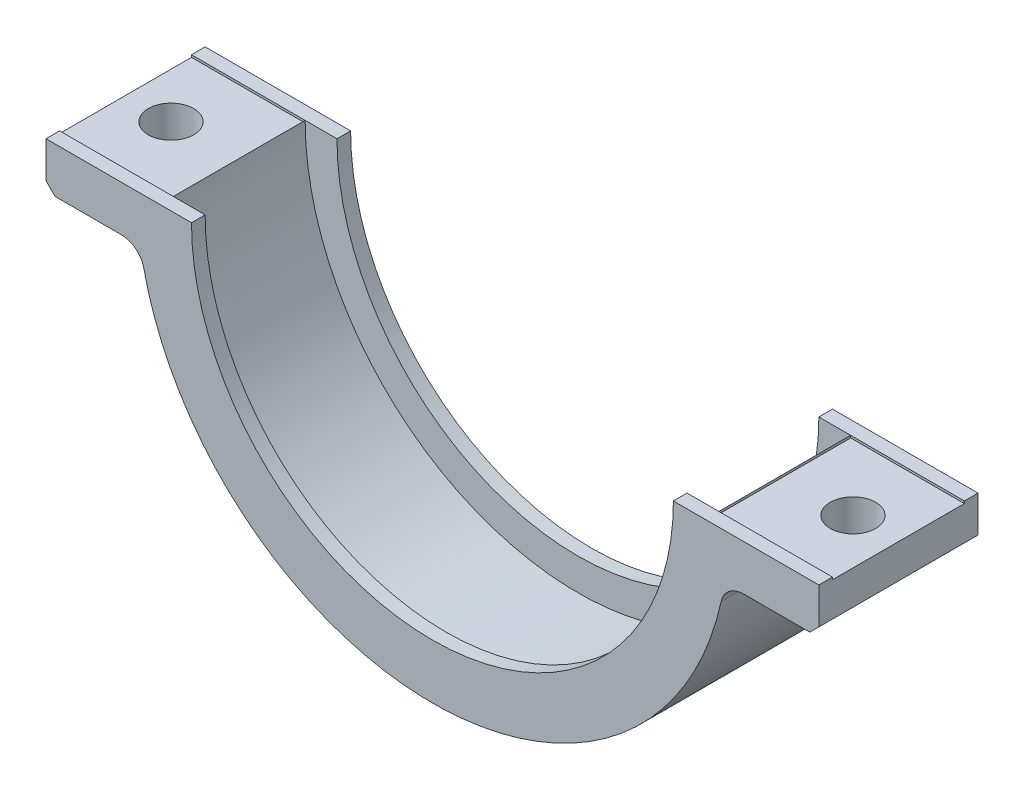
SolidWorks part; units mm, degrees
ref_plane "Płaszczyzna przednia" through (0, 0, 0) normal (0, 0, 1) x (1, 0, 0)
ref_plane "Płaszczyzna górna" through (0, 0, 0) normal (0, 1, 0) x (1, 0, 0)
ref_plane "Płaszczyzna prawa" through (0, 0, 0) normal (1, 0, 0) x (0, 0, -1)
sketch "Szkic1" plane through (0, 0, 0) normal (0, 0, 1) x (1, 0, 0)
  line L0 (-65, 0) -> (-60, 0)
  line L1 (60, 0) -> (65, 0)
  line L2 (-65, 0) -> (-85, 0)
  line L3 (-85, 0) -> (-85, -8)
  line L4 (-83, -10) -> (-68.374, -10)
  line L5 (0, 0) -> (0, -5.7324)
  line L6 (83, -10) -> (68.374, -10)
  line L7 (85, 0) -> (85, -8)
  line L8 (65, 0) -> (85, 0)
  line L9 (-85, -8) -> (-83, -10)
  line L10 (85, -8) -> (83, -10)
  arc A0 (-60, 0) -> (60, 0) centre (0, 0) ccw
  arc A1 (-63.4901, -13.9286) -> (63.4901, -13.9286) centre (0, 0) ccw
  circle A2 centre (0, 0) radius 65 construction
  circle A3 centre (0, 0) radius 60 construction
  arc A4 (68.374, -10) -> (63.4901, -13.9286) centre (68.374, -15) ccw
  arc A5 (-68.374, -10) -> (-63.4901, -13.9286) centre (-68.374, -15) cw
  point P2 (85, -10)
  point P11 (-85, -10)
  point P18 (64.2262, -10)
  point P21 (-64.2262, -10)
  dimension "D1" = 120
  dimension "D5" = 5
  dimension "D3" = 20
  dimension "D4" = 10
  dimension "D2" = 5
extrude "Dodanie-wyciągnięcie1" add sketch "Szkic1" along normal mid plane 29 contours L4 A5 A1 A4 L6 L10 L7 L8 L1 A0 L0 L2 L3 L9
sketch "Szkic2" plane through (0, 0, 14.5) normal (0, 0, 1) x (1, 0, 0)
  line L0 (-65, 0) -> (-60, 0)
  line L1 (60, 0) -> (65, 0)
  line L2 (-65, 0) -> (-85, 0)
  line L3 (-85, 0) -> (-85, -8)
  line L4 (-83, -10) -> (-68.374, -10)
  line L6 (83, -10) -> (68.374, -10)
  line L7 (85, 0) -> (85, -8)
  line L8 (65, 0) -> (85, 0)
  line L9 (-85, -8) -> (-83, -10)
  line L10 (85, -8) -> (83, -10)
  line L11 (-60, 0) -> (-53, 0)
  line L12 (53, 0) -> (60, 0)
  arc A1 (-63.4901, -13.9286) -> (63.4901, -13.9286) centre (0, 0) ccw
  arc A2 (68.374, -10) -> (63.4901, -13.9286) centre (68.374, -15) ccw
  arc A3 (-68.374, -10) -> (-63.4901, -13.9286) centre (-68.374, -15) cw
  arc A4 (-53, 0) -> (53, 0) centre (0, 0) ccw
  point P1 (85, -10)
  point P8 (-85, -10)
  dimension "D4" = 5
  dimension "D9" = 106
  dimension "D2" = 20
  dimension "D3" = 10
  dimension "D5" = 2
  dimension "D6" = 2
  dimension "D7" = 2
  dimension "D8" = 2
extrude "Dodanie-wyciągnięcie2" add sketch "Szkic2" along normal blind 3
sketch "Szkic3" plane through (0, 0, -14.5) normal (0, 0, -1) x (-1, 0, 0)
  line L0 (-65, 0) -> (-60, 0)
  line L1 (60, 0) -> (65, 0)
  line L2 (-65, 0) -> (-85, 0)
  line L3 (-85, 0) -> (-85, -8)
  line L4 (-83, -10) -> (-68.374, -10)
  line L5 (83, -10) -> (68.374, -10)
  line L6 (85, 0) -> (85, -8)
  line L7 (65, 0) -> (85, 0)
  line L8 (-85, -8) -> (-83, -10)
  line L9 (85, -8) -> (83, -10)
  line L10 (-60, 0) -> (-53, 0)
  line L11 (53, 0) -> (60, 0)
  arc A0 (-63.4901, -13.9286) -> (63.4901, -13.9286) centre (0, 0) ccw
  arc A1 (68.374, -10) -> (63.4901, -13.9286) centre (68.374, -15) ccw
  arc A2 (-68.374, -10) -> (-63.4901, -13.9286) centre (-68.374, -15) cw
  arc A3 (-53, 0) -> (53, 0) centre (0, 0) ccw
  point P1 (85, -10)
  point P8 (-85, -10)
  dimension "D3" = 5
  dimension "D8" = 106
  dimension "D1" = 20
  dimension "D2" = 10
  dimension "D4" = 2
  dimension "D5" = 2
  dimension "D6" = 2
  dimension "D7" = 2
extrude "Dodanie-wyciągnięcie3" add sketch "Szkic3" along normal blind 3
hole_wizard "Otwór Ø10.0 (10)1" positions "Szkic5" profile "Szkic4" hole size "Ø10.0" standard "DIN" end condition through all
sketch "Szkic5" plane through (0, 0, 0) normal (0, 1, 0) x (1, 0, 0)
  line L0 (-60, -14.5) -> (-60, 14.5) construction
  line L1 (60, -14.5) -> (60, 14.5) construction
  point P0 (75, 0)
  point P2 (-75, 0)
  dimension "D1" = 15
  dimension "D2" = 15
sketch "Szkic4" plane through (75, 0, 0) normal (1, 0, 0) x (0, 0, 1)
  line L0 (0, 0) -> (0, 65)
  line L1 (0, 65) -> (5, 65)
  line L2 (5, 65) -> (5, 0)
  line L5 (5, 0) -> (0, 0)
  line L11 (0, -6.35) -> (0, 107.95) construction
  dimension "Średnica otworu na wylot" = 10
  dimension "Głębokość otworu na wylot" = 65
ref_plane "Płaszczyzna1" through (-60, 0, 14.5) normal (0, 0, -1) x (-1, 0, 0)
sketch "Szkic7" plane through (0, 0, 0) normal (0, 1, 0) x (1, 0, 0)
  line L0 (-60, 14.5) -> (-85, 14.5)
  line L1 (-85, -17.5) -> (-85, 17.5) construction
  line L2 (-85, 14.5) -> (-85, -14.5)
  line L3 (-85, -14.5) -> (-60, -14.5)
  line L4 (-60, -14.5) -> (-60, 14.5)
  line L5 (-60, 14.5) -> (-60.3696, 15.0497)
  line L6 (60, 14.5) -> (60, -14.5)
  line L7 (60, -14.5) -> (85, -14.5)
  line L8 (85, -17.5) -> (85, 17.5) construction
  line L9 (85, -14.5) -> (85, 14.5)
  line L10 (85, 14.5) -> (60, 14.5)
  circle M1 centre (-75, 0) radius 5
  line M2 (-60, -14.5) -> (-60, 14.5)
  line M6 (-85, 17.5) -> (-85, -17.5)
extrude "Wytnij-wyciągnięcie1" cut sketch "Szkic7" against normal blind 0.5 contours L3 L0 M6 M2 M1 | L9 L10 L6 L7
